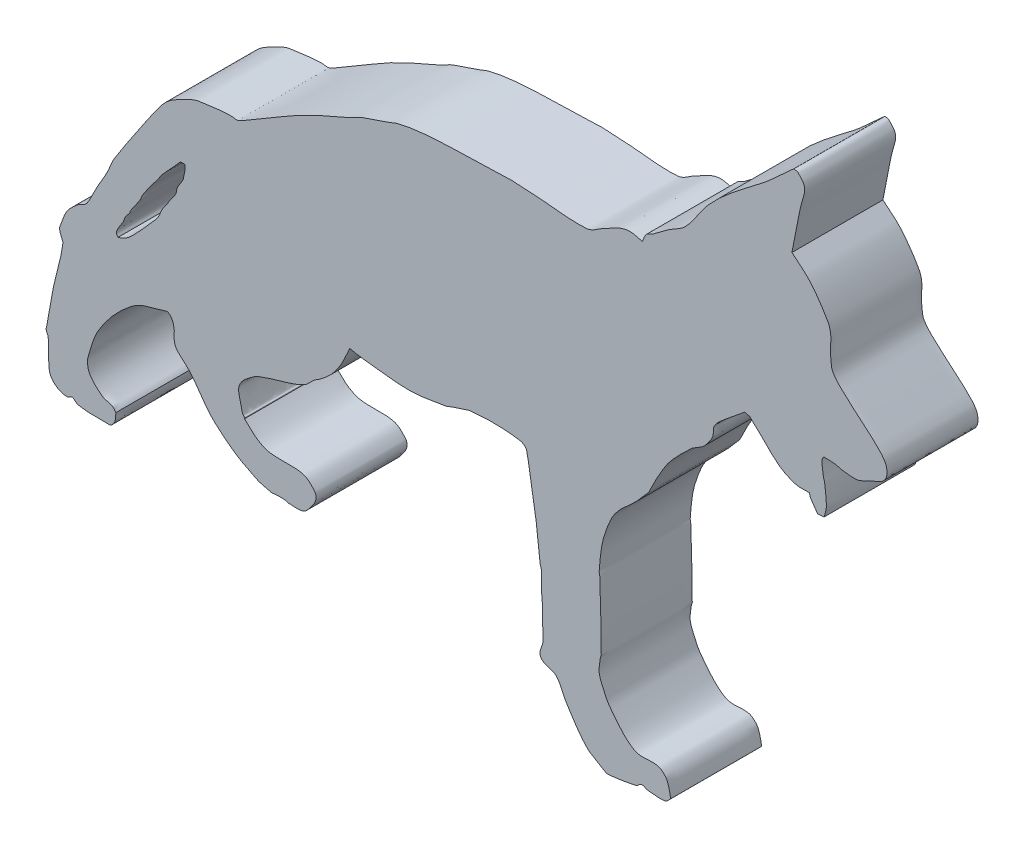
SolidWorks part; units mm, degrees
ref_plane "Front Plane" through (0, 0, 0) normal (0, 0, 1) x (1, 0, 0)
ref_plane "Top Plane" through (0, 0, 0) normal (0, 1, 0) x (1, 0, 0)
ref_plane "Right Plane" through (0, 0, 0) normal (1, 0, 0) x (0, 0, -1)
sketch "Sketch1" plane through (0, 0, 0) normal (0, 0, 1) x (1, 0, 0)
  line L4 (45.9802, 22.7444) -> (45.6202, 22.7144)
  line L5 (58.4707, 12.1459) -> (58.4707, 46.1648)
  line L6 (58.4707, 46.1648) -> (5.7862, 46.1648)
  spline S0 degree 3 poles (19.9252, 17.7344) (19.7355, 17.322) (19.5672, 16.8936) (19.3102, 16.5194) (19.1812, 16.3314) (19.048, 16.1441) (18.8902, 15.9794) (18.7015, 15.7825) (18.4896, 15.6081) (18.2752, 15.4394) (18.1836, 15.3673) (18.0666, 15.3319) (17.9752, 15.2594) (17.7755, 15.101) (17.6298, 14.8702) (17.4052, 14.7494) (16.7814, 14.4139) (16.0632, 14.2952) (15.3952, 14.0594) (15.1457, 13.9713) (14.8764, 13.912) (14.6602, 13.7594) (14.3569, 13.5453) (14.014, 13.3195) (13.8652, 12.9794) (13.7447, 12.704) (13.8663, 12.3742) (13.9252, 12.0794) (14.0893, 11.2592) (14.2039, 11.769) (14.1352, 11.4944) knots 0 0 0 0 1 1 1 2 2 2 3 3 3 4 4 4 5 5 5 6 6 6 7 7 7 8 8 8 9 9 9 10 10 10 10
  spline S1 degree 3 poles (45.9502, 25.5944) (45.9202, 25.5244) (45.8615, 25.4606) (45.8602, 25.3844) (45.8563, 25.1432) (45.9001, 24.9032) (45.9352, 24.6644) (45.9502, 24.5624) (45.998, 24.4668) (46.0102, 24.3644) (46.0531, 24.0057) (46.1069, 23.6456) (46.1002, 23.2844) (46.0968, 23.1001) (46.0202, 22.9244) (45.9802, 22.7444) knots 0 0 0 0 1 1 1 2 2 2 3 3 3 4 4 4 5 5 5 5
  spline S2 degree 3 poles (45.6202, 22.7144) (45.4902, 22.9044) (45.3453, 23.085) (45.2302, 23.2844) (45.1939, 23.3475) (45.1902, 23.4244) (45.1702, 23.4944) knots 0 0 0 0 1 1 1 2 2 2 2
  spline S3 degree 3 poles (14.1352, 11.4944) (14.3652, 11.2894) (14.5685, 11.0497) (14.8252, 10.8794) (15.0343, 10.7408) (15.2676, 10.6194) (15.5152, 10.5794) (16.1135, 10.4827) (16.7421, 10.6206) (17.3302, 10.4744) (17.6001, 10.4074) (17.8148, 10.1801) (17.9902, 9.9644) (18.0701, 9.8662) (18.0777, 9.713) (18.0502, 9.5894) (18.0143, 9.4278) (17.9131, 9.2842) (17.8102, 9.1544) (17.6806, 8.991) (17.556, 8.7917) (17.3602, 8.7194) (17.1068, 8.6259) (16.8203, 8.6817) (16.5502, 8.6894) (16.4678, 8.6918) (16.3926, 8.7456) (16.3102, 8.7494) (15.5168, 8.786) (15.8162, 8.6706) (15.5152, 8.7494) (15.3252, 8.7992) (15.13, 8.8325) (14.9452, 8.8994) (14.7833, 8.9581) (14.6331, 9.0452) (14.4802, 9.1244) (14.228, 9.2552) (13.968, 9.3738) (13.7302, 9.5294) (13.4165, 9.7348) (13.1167, 9.9624) (12.8302, 10.2044) (12.6006, 10.3984) (12.3778, 10.6037) (12.1852, 10.8344) (11.8213, 11.2705) (11.5306, 11.7646) (11.1652, 12.1994) (10.9241, 12.4863) (10.5758, 12.681) (10.3702, 12.9944) (10.2584, 13.165) (10.2755, 13.392) (10.2502, 13.5944) (10.2451, 13.6353) (10.2838, 13.6733) (10.2802, 13.7144) (10.2614, 13.9343) (10.2238, 14.1839) (10.0702, 14.3594) (10.0227, 14.4137) (9.9502, 14.4394) (9.8902, 14.4794) knots 0 0 0 0 1 1 1 2 2 2 3 3 3 4 4 4 5 5 5 6 6 6 7 7 7 8 8 8 9 9 9 10 10 10 11 11 11 12 12 12 13 13 13 14 14 14 15 15 15 16 16 16 17 17 17 18 18 18 19 19 19 20 20 20 21 21 21 21
  spline S4 degree 3 poles (45.1702, 23.4944) (44.9152, 23.5044) (44.65, 23.4521) (44.4052, 23.5244) (44.0621, 23.6259) (43.7279, 23.7851) (43.4452, 24.0044) (42.8947, 24.4315) (42.4626, 24.995) (41.9302, 25.4444) (41.8457, 25.5158) (41.7202, 25.5144) (41.6152, 25.5494) knots 0 0 0 0 1 1 1 2 2 2 3 3 3 4 4 4 4
  spline S5 degree 3 poles (37.5502, 5.1194) (37.4452, 5.0344) (37.3682, 4.8884) (37.2352, 4.8644) (36.93, 4.8093) (36.6137, 4.8621) (36.3052, 4.8944) (36.1809, 4.9074) (36.0691, 5.0163) (35.9452, 4.9994) (35.8271, 4.9833) (35.7614, 4.8316) (35.6452, 4.8044) (35.1329, 4.6846) (34.6102, 4.5991) (34.0852, 4.5644) (33.9915, 4.5582) (33.9102, 4.6352) (33.8302, 4.6844) (33.5196, 4.8756) (33.1664, 5.0199) (32.9152, 5.2844) (32.4958, 5.7261) (32.1825, 6.2589) (31.8502, 6.7694) (31.6317, 7.1052) (31.5422, 7.53) (31.2652, 7.8194) (31.075, 8.0182) (30.7269, 7.9886) (30.5152, 8.1644) (30.1719, 8.4496) (30.5279, 8.8047) (30.5302, 9.1094) (30.5348, 9.7095) (30.519, 10.3096) (30.5002, 10.9094) (30.4989, 10.9506) (30.4718, 10.9882) (30.4702, 11.0294) (30.4518, 11.5092) (30.4659, 11.99) (30.4402, 12.4694) (30.4358, 12.5518) (30.3908, 12.6276) (30.3802, 12.7094) (30.2957, 13.3633) (30.2328, 14.0197) (30.1552, 14.6744) (30.1528, 14.6949) (30.1436, 14.7141) (30.1402, 14.7344) (29.9986, 15.5991) (29.8635, 16.465) (29.7202, 17.3294) (29.7135, 17.3701) (29.7008, 17.4096) (29.6902, 17.4494) (29.6558, 17.5796) (29.669, 17.734) (29.5852, 17.8394) (29.5003, 17.9463) (29.3599, 18.0123) (29.2252, 18.0344) (28.7405, 18.1139) (28.2465, 18.134) (27.7552, 18.1394) (27.3345, 18.144) (26.915, 18.093) (26.4952, 18.0644) (26.4747, 18.063) (26.4548, 18.0559) (26.4352, 18.0494) (26.2597, 17.9909) (26.0868, 17.9248) (25.9102, 17.8694) (25.8316, 17.8447) (25.7485, 17.8355) (25.6702, 17.8094) (25.4887, 17.7489) (25.3198, 17.6408) (25.1302, 17.6144) (24.5405, 17.5322) (23.9554, 17.391) (23.3602, 17.3744) (22.6534, 17.3547) (21.9461, 17.4454) (21.2452, 17.5394) (20.8044, 17.5986) (20.3529, 17.6122) (19.9252, 17.7344) knots 0 0 0 0 1 1 1 2 2 2 3 3 3 4 4 4 5 5 5 6 6 6 7 7 7 8 8 8 9 9 9 10 10 10 11 11 11 12 12 12 13 13 13 14 14 14 15 15 15 16 16 16 17 17 17 18 18 18 19 19 19 20 20 20 21 21 21 22 22 22 23 23 23 24 24 24 25 25 25 26 26 26 27 27 27 28 28 28 29 29 29 30 30 30 30
  spline S20 degree 3 poles (35.9902, 30.8594) (36.0652, 31.0094) (36.1026, 31.1852) (36.2152, 31.3094) (36.3069, 31.4105) (36.4625, 31.4275) (36.5752, 31.5044) (36.8734, 31.708) (37.1491, 31.9429) (37.4452, 32.1494) (37.7444, 32.3581) (38.1076, 32.4863) (38.3602, 32.7494) (38.8374, 33.2465) (39.1517, 33.8807) (39.6052, 34.3994) (40.2628, 35.1515) (41.0654, 35.7677) (41.8552, 36.3794) (42.1905, 36.6391) (42.5376, 36.8843) (42.8602, 37.1594) (43.3531, 37.5797) (43.8161, 38.0341) (44.3002, 38.4644) (44.3121, 38.4749) (44.33, 38.4837) (44.3452, 38.4794) (44.4231, 38.4578) (44.5154, 38.4487) (44.5702, 38.3894) (44.7077, 38.2408) (44.8817, 38.0811) (44.9002, 37.8794) (44.9357, 37.4927) (44.7364, 37.1202) (44.6602, 36.7394) (44.5076, 35.9762) (44.3495, 35.2106) (44.2102, 34.4444) knots 0 0 0 0 1 1 1 2 2 2 3 3 3 4 4 4 5 5 5 6 6 6 7 7 7 8 8 8 9 9 9 10 10 10 11 11 11 12 12 12 13 13 13 13
  spline S21 degree 3 poles (9.8902, 14.4794) (9.6102, 14.3944) (9.3308, 14.3077) (9.0502, 14.2244) (8.8757, 14.1726) (8.6917, 14.1479) (8.5252, 14.0744) (8.304, 13.9767) (8.0846, 13.8649) (7.8952, 13.7144) (7.5462, 13.4372) (7.215, 13.1338) (6.9202, 12.7994) (6.6174, 12.4558) (6.3433, 12.0838) (6.1102, 11.6894) (5.9, 11.3337) (5.7684, 10.9332) (5.6602, 10.5344) (5.6063, 10.3355) (5.5128, 10.1406) (5.5102, 9.9344) (5.5077, 9.7343) (5.5384, 9.5187) (5.6452, 9.3494) (5.8132, 9.0833) (6.0498, 8.8582) (6.3052, 8.6744) (6.4696, 8.5562) (6.6977, 8.5619) (6.8752, 8.4644) (6.959, 8.4184) (7.0052, 8.3244) (7.0702, 8.2544) knots 0 0 0 0 1 1 1 2 2 2 3 3 3 4 4 4 5 5 5 6 6 6 7 7 7 8 8 8 9 9 9 10 10 10 11 11 11 11
  spline S22 degree 3 poles (4.6852, 7.8044) (4.5802, 7.7594) (4.4845, 7.6694) (4.3702, 7.6694) (4.204, 7.6694) (4.0321, 7.7178) (3.8902, 7.8044) (3.7273, 7.9039) (3.5727, 8.0397) (3.4852, 8.2094) (3.3945, 8.3855) (3.3954, 8.5969) (3.3802, 8.7944) (3.3503, 9.1834) (3.3887, 9.5762) (3.3502, 9.9644) (3.3382, 10.0856) (3.2534, 10.1899) (3.2302, 10.3094) (3.2224, 10.3499) (3.2528, 10.3889) (3.2602, 10.4294) (3.3878, 11.124) (3.5089, 11.8197) (3.6352, 12.5144) (3.6389, 12.5347) (3.6458, 12.5543) (3.6502, 12.5744) (3.8208, 13.3493) (4.0717, 14.1109) (4.1602, 14.8994) (4.1645, 14.937) (3.9101, 15.3648) (3.9952, 15.5744) (4.1176, 15.8755) (4.1937, 16.2016) (4.3702, 16.4744) (4.5297, 16.7208) (4.7613, 16.9147) (4.9852, 17.1044) (5.1239, 17.2219) (5.3379, 17.2465) (5.4502, 17.3894) (5.6783, 17.6797) (5.7962, 18.0416) (5.9752, 18.3644) (6.1762, 18.7267) (6.3977, 19.0776) (6.5902, 19.4444) (6.7358, 19.7218) (6.8151, 20.0332) (6.9802, 20.2994) (7.2982, 20.8121) (7.6333, 21.314) (7.9702, 21.8144) (8.4683, 22.5541) (8.9527, 23.3041) (9.4852, 24.0194) (9.6394, 24.2265) (9.8202, 24.4176) (10.0252, 24.5744) (10.2494, 24.7458) (10.5089, 24.8661) (10.7602, 24.9944) (11.0521, 25.1435) (11.3497, 25.316) (11.6752, 25.3544) (12.2494, 25.4222) (12.8221, 25.5344) (13.4002, 25.5344) (13.5303, 25.5344) (13.6682, 25.4742) (13.7902, 25.5194) (14.0863, 25.6291) (14.3406, 25.8288) (14.6152, 25.9844) (14.9406, 26.1688) (15.2664, 26.3524) (15.5902, 26.5394) (16.0714, 26.8174) (16.5389, 27.1198) (17.0302, 27.3794) (17.5997, 27.6803) (18.1854, 27.9497) (18.7702, 28.2194) (19.1506, 28.3948) (19.545, 28.5387) (19.9252, 28.7144) (20.1404, 28.8139) (20.3347, 28.9575) (20.5552, 29.0444) (21.0215, 29.2282) (21.5073, 29.3585) (21.9802, 29.5244) (22.1774, 29.5936) (22.3624, 29.6995) (22.5652, 29.7494) (23.4451, 29.9658) (24.3599, 30.0279) (25.2652, 30.0644) (26.3899, 30.1098) (27.5154, 30.1301) (28.6402, 30.1694) (28.6608, 30.1701) (28.6796, 30.1852) (28.7002, 30.1844) (29.2207, 30.1644) (29.7403, 30.1258) (30.2602, 30.0944) (31.15, 30.0406) (32.0422, 29.8667) (32.9302, 29.9444) (33.2755, 29.9746) (33.552, 30.251) (33.8602, 30.4094) (34.087, 30.526) (34.3065, 30.6567) (34.5352, 30.7694) (34.6618, 30.8318) (34.7891, 30.8973) (34.9252, 30.9344) (35.0664, 30.9729) (35.2142, 31.0047) (35.3602, 30.9944) (35.5745, 30.9793) (35.7802, 30.9044) (35.9902, 30.8594) knots 0 0 0 0 1 1 1 2 2 2 3 3 3 4 4 4 5 5 5 6 6 6 7 7 7 8 8 8 9 9 9 10 10 10 11 11 11 12 12 12 13 13 13 14 14 14 15 15 15 16 16 16 17 17 17 18 18 18 19 19 19 20 20 20 21 21 21 22 22 22 23 23 23 24 24 24 25 25 25 26 26 26 27 27 27 28 28 28 29 29 29 30 30 30 31 31 31 32 32 32 33 33 33 34 34 34 35 35 35 36 36 36 37 37 37 38 38 38 39 39 39 40 40 40 41 41 41 42 42 42 42
  spline S23 degree 3 poles (41.6152, 25.5494) (41.3252, 25.3144) (41.0252, 25.0913) (40.7452, 24.8444) (40.4747, 24.6059) (40.1623, 24.3965) (39.9652, 24.0944) (39.8485, 23.9154) (39.9333, 23.6592) (39.8452, 23.4644) (39.7389, 23.2293) (39.5675, 23.0266) (39.3952, 22.8344) (39.3044, 22.7331) (39.178, 22.6704) (39.0652, 22.5944) (38.9479, 22.5153) (38.8087, 22.4659) (38.7052, 22.3694) (38.2864, 21.9787) (37.8684, 21.5823) (37.5052, 21.1394) (37.2502, 20.8284) (37.0626, 20.4671) (36.8602, 20.1194) (36.7073, 19.8566) (36.5808, 19.5791) (36.4402, 19.3094) (36.3958, 19.2241) (36.3659, 19.129) (36.3052, 19.0544) (36.0595, 18.7523) (35.798, 18.4625) (35.5252, 18.1844) (35.2824, 17.9369) (34.9925, 17.7369) (34.7602, 17.4794) (34.5753, 17.2744) (34.3985, 17.0539) (34.2802, 16.8044) (34.0756, 16.3729) (33.9085, 15.9196) (33.8002, 15.4544) (33.6872, 14.9688) (33.6666, 14.4659) (33.6202, 13.9694) (33.6164, 13.9284) (33.649, 13.8906) (33.6502, 13.8494) (33.689, 12.5997) (33.7308, 11.3497) (33.7402, 10.0994) (33.7409, 10.017) (33.6908, 9.9412) (33.6802, 9.8594) (33.6507, 9.6304) (33.5962, 9.399) (33.6202, 9.1694) (33.6421, 8.9603) (33.7294, 8.7614) (33.8152, 8.5694) (33.9403, 8.2896) (34.0563, 7.9968) (34.2502, 7.7594) (34.6417, 7.2802) (35.0136, 6.7386) (35.5552, 6.4394) (35.9285, 6.2332) (36.414, 6.4273) (36.8302, 6.3344) (36.9886, 6.2991) (37.1234, 6.182) (37.2352, 6.0644) (37.3246, 5.9704) (37.3742, 5.8425) (37.4152, 5.7194) (37.4801, 5.5249) (37.5052, 5.3194) (37.5502, 5.1194) knots 0 0 0 0 1 1 1 2 2 2 3 3 3 4 4 4 5 5 5 6 6 6 7 7 7 8 8 8 9 9 9 10 10 10 11 11 11 12 12 12 13 13 13 14 14 14 15 15 15 16 16 16 17 17 17 18 18 18 19 19 19 20 20 20 21 21 21 22 22 22 23 23 23 24 24 24 25 25 25 26 26 26 26
  spline S24 degree 3 poles (7.1902, 16.6544) (7.1602, 16.7044) (7.0984, 16.7461) (7.1002, 16.8044) (7.1089, 17.0743) (7.3648, 17.3127) (7.4752, 17.5394) (7.5224, 17.6362) (7.5405, 17.7466) (7.5952, 17.8394) (7.6567, 17.9437) (7.7548, 18.0226) (7.8202, 18.1244) (7.8459, 18.1643) (7.8417, 18.2182) (7.8652, 18.2594) (8.0276, 18.5436) (8.2501, 18.7898) (8.4202, 19.0694) (8.4507, 19.1194) (8.4524, 19.1829) (8.4802, 19.2344) (8.7304, 19.6973) (9.0718, 20.0874) (9.3802, 20.5094) (9.4506, 20.6057) (9.4996, 20.7172) (9.5752, 20.8094) (9.7053, 20.9681) (9.8575, 21.1073) (9.9952, 21.2594) (10.1925, 21.4773) (10.3702, 21.7137) (10.5802, 21.9194) (10.6141, 21.9526) (10.6679, 21.9619) (10.7152, 21.9644) (10.7662, 21.9671) (10.8521, 21.9837) (10.8652, 21.9344) knots 0 0 0 0 1 1 1 2 2 2 3 3 3 4 4 4 5 5 5 6 6 6 7 7 7 8 8 8 9 9 9 10 10 10 11 11 11 12 12 12 13 13 13 13
  spline S25 degree 3 poles (44.2102, 34.4444) (44.5402, 34.1494) (44.9103, 33.8939) (45.2002, 33.5594) (45.5645, 33.1391) (45.8795, 32.6746) (46.1602, 32.1944) (46.2632, 32.0183) (46.319, 31.8123) (46.3402, 31.6094) (46.3767, 31.2613) (46.2815, 30.9045) (46.3402, 30.5594) (46.3768, 30.3447) (46.3478, 30.1093) (46.4452, 29.9144) (46.5755, 29.6539) (46.7903, 29.4414) (47.0002, 29.2394) (47.5873, 28.6745) (48.2542, 28.1955) (48.8302, 27.6194) (49.0579, 27.3917) (49.3214, 27.1517) (49.4002, 26.8394) (49.5061, 26.4202) (49.355, 26.1052) (49.0402, 25.9544) (48.8644, 25.8702) (48.6776, 25.8103) (48.5002, 25.7294) (48.3924, 25.6802) (48.2942, 25.6111) (48.1852, 25.5644) (48.0486, 25.5059) (47.9135, 25.4251) (47.7652, 25.4144) (47.4902, 25.3945) (47.2138, 25.4398) (46.9402, 25.4744) (46.8175, 25.49) (46.703, 25.5495) (46.5802, 25.5644) (46.3715, 25.5897) (46.1602, 25.5844) (45.9502, 25.5944) knots 0 0 0 0 1 1 1 2 2 2 3 3 3 4 4 4 5 5 5 6 6 6 7 7 7 8 8 8 9 9 9 10 10 10 11 11 11 12 12 12 13 13 13 14 14 14 15 15 15 15
  spline S26 degree 3 poles (7.0702, 8.2544) (7.0452, 8.0894) (7.0699, 7.9087) (6.9952, 7.7594) (6.9319, 7.6328) (6.8186, 7.5044) (6.6802, 7.4744) (4.6276, 7.0293) (6.1243, 7.4448) (5.6902, 7.5044) (5.4555, 7.5366) (5.2122, 7.5267) (4.9852, 7.5944) (4.8683, 7.6293) (4.7852, 7.7344) (4.6852, 7.8044) knots 0 0 0 0 1 1 1 2 2 2 3 3 3 4 4 4 5 5 5 5
  spline S27 degree 3 poles (10.8652, 21.9344) (10.9014, 21.7988) (10.8526, 21.6537) (10.8352, 21.5144) (10.8325, 21.4922) (10.8096, 21.4763) (10.8052, 21.4544) (10.7894, 21.3754) (10.808, 21.2881) (10.7752, 21.2144) (10.6861, 21.0138) (10.5368, 20.8439) (10.4452, 20.6444) (10.3957, 20.5364) (10.4092, 20.4053) (10.3552, 20.2994) (10.2671, 20.1264) (10.1314, 19.982) (10.0252, 19.8194) (9.9713, 19.7369) (9.9299, 19.6465) (9.8752, 19.5644) (9.7998, 19.4512) (9.7031, 19.3523) (9.6352, 19.2344) (9.5325, 19.0562) (9.4782, 18.8513) (9.3652, 18.6794) (9.2464, 18.4986) (9.088, 18.347) (8.9452, 18.1844) (8.728, 17.937) (8.5123, 17.6879) (8.2852, 17.4494) (7.9491, 17.0963) (7.6712, 16.7654) (7.1902, 16.6544) knots 13 13 13 13 14 14 14 15 15 15 16 16 16 17 17 17 18 18 18 19 19 19 20 20 20 21 21 21 22 22 22 23 23 23 24 24 24 25 25 25 25
  dimension "D3" = 52.6845
  dimension "D4" = 34.019
extrude "Boss-Extrude1" add sketch "Sketch1" along normal blind 5 contours S26 S21 S3 S0 S5 S23 S4 S2 L4 S1 S25 S20 S22 S24 S27
sketch "Sketch2" plane through (0, 0, 0) normal (0, 0, -1) x (-1, 0, 0)
  line L0 (-5.6069, 7.5143) -> (-6.7537, 7.5002)
  spline S0 degree 3 poles (-7.0702, 8.2544) (-7.0452, 8.0894) (-7.0699, 7.9087) (-6.9952, 7.7594) (-6.9319, 7.6328) (-6.8186, 7.5044) (-6.6802, 7.4744) (-4.6276, 7.0293) (-6.1243, 7.4448) (-5.6902, 7.5044) (-5.4555, 7.5366) (-5.2122, 7.5267) (-4.9852, 7.5944) (-4.8683, 7.6293) (-4.7852, 7.7344) (-4.6852, 7.8044) knots 0 0 0 0 1 1 1 2 2 2 3 3 3 4 4 4 5 5 5 5 construction
extrude "Cut-Extrude1" cut sketch "Sketch2" against normal blind 5 and the other way through all
sketch "Sketch6" plane through (0, 0, 5) normal (0, 0, 1) x (1, 0, 0)
  line L0 (53.3027, 3.7712) -> (53.3027, 40.4911)
  line L1 (53.3027, 40.4911) -> (0.8698, 40.4911)
  dimension "D1" = 52.4329
  dimension "D2" = 36.7199
